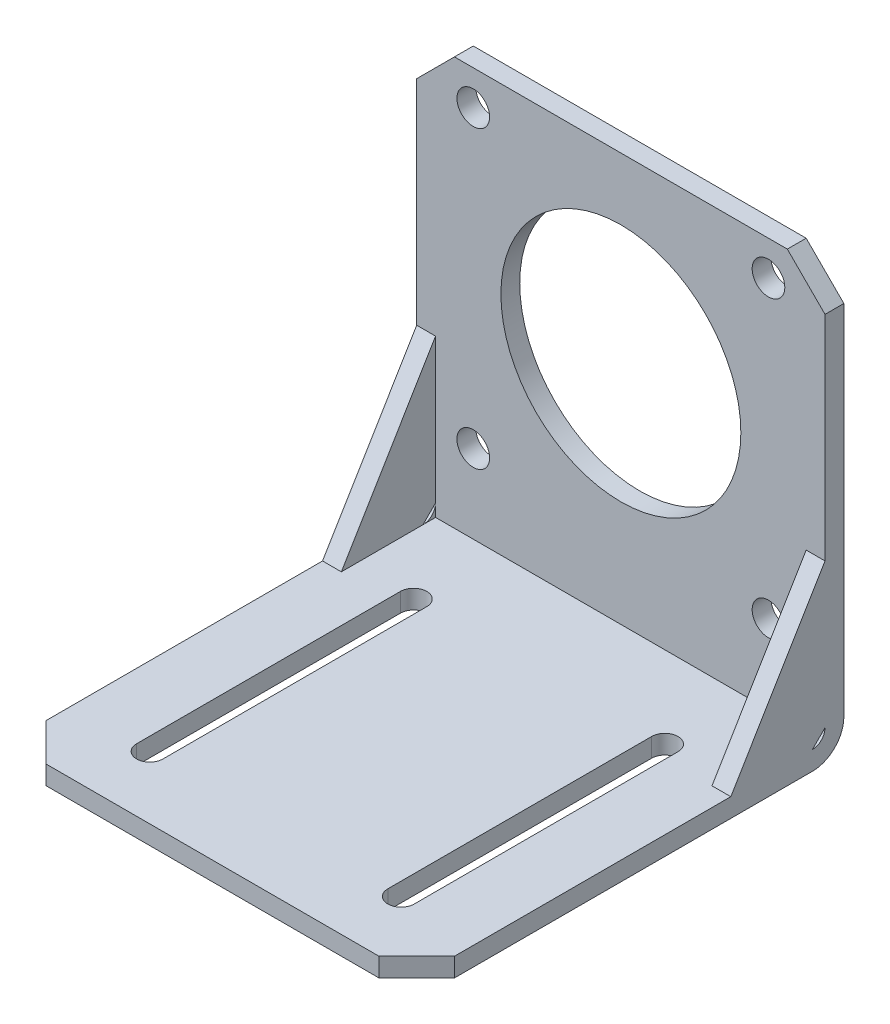
SolidWorks part; units mm, degrees
ref_plane "Front Plane" through (0, 0, 0) normal (0, 0, 1) x (1, 0, 0)
ref_plane "Top Plane" through (0, 0, 0) normal (0, 1, 0) x (1, 0, 0)
ref_plane "Right Plane" through (0, 0, 0) normal (1, 0, 0) x (0, 0, -1)
sketch "Sketch1" plane through (0, 0, 0) normal (0, 0, 1) x (1, 0, 0)
  line L0 (0, 65) -> (0, 36) construction
  line L1 (-32.5, 59) -> (-32.5, 0)
  line L2 (32.5, -65) -> (32.5, 65) construction
  line L3 (32.5, 65) -> (-32.5, 65) construction
  line L4 (-32.5, -65) -> (-32.5, 65) construction
  line L5 (32.5, -65) -> (-32.5, 65) construction
  line L6 (32.5, 65) -> (-32.5, -65) construction
  line L7 (-32.5, 65) -> (-23.5, 65) construction
  line L8 (32.5, 65) -> (23.5, 65) construction
  line L9 (-32.5, 0) -> (32.5, 0)
  line L10 (23.5, 59.5) -> (-23.5, 59.5) construction
  line L11 (23.5, 59.5) -> (23.5, 12.5) construction
  line L12 (23.5, 12.5) -> (-23.5, 12.5) construction
  line L13 (-23.5, 59.5) -> (-23.5, 12.5) construction
  line L14 (23.5, 59.5) -> (-23.5, 12.5) construction
  line L15 (23.5, 12.5) -> (-23.5, 59.5) construction
  line L16 (32.5, 0) -> (32.5, 59)
  line L33 (32.5, 65) -> (26.5, 65) construction
  line L34 (32.5, 65) -> (32.5, 59) construction
  line L35 (32.5, 59) -> (26.5, 65)
  line L36 (-32.5, 65) -> (-26.5, 65) construction
  line L37 (-32.5, 65) -> (-32.5, 59) construction
  line L38 (-32.5, 59) -> (-26.5, 65)
  line L39 (-26.5, 65) -> (26.5, 65)
  line L43 (-32.5, 65) -> (-32.5, 0) construction
  line L44 (-32.5, 0) -> (32.5, 0) construction
  circle A0 centre (0, 36) radius 19.1
  circle A1 centre (-23.5, 59.5) radius 2.6
  circle A2 centre (23.5, 59.5) radius 2.6
  circle A3 centre (23.5, 12.5) radius 2.6
  circle A4 centre (-23.5, 12.5) radius 2.6
  point P0 (0, 0)
extrude "Boss-Extrude1" add sketch "Sketch1" along normal blind 3
sketch "Sketch2" plane through (-32.5, 0, 0) normal (-1, 0, 0) x (0, 0, 1)
  line L0 (0, 0) -> (0, -3)
  line L1 (0, -3) -> (68, -3)
  line L2 (68, -3) -> (68, 0)
  line L3 (68, 0) -> (0, 0)
extrude "Boss-Extrude2" add sketch "Sketch2" against normal blind 65
sketch "Sketch3" plane through (-32.5, 0, 0) normal (-1, 0, 0) x (0, 0, 1)
  line L0 (3, 0) -> (18, 0) construction
  line L1 (68, 0) -> (3, 0) construction
  line L2 (3, 0) -> (3, 25) construction
  line L3 (3, 59) -> (3, 0) construction
  line L4 (3, 25) -> (18, 0)
  line L5 (18, 0) -> (3, 0)
  line L6 (3, 0) -> (3, 25)
extrude "Boss-Extrude3" add sketch "Sketch3" against normal blind 3
sketch "Sketch4" plane through (32.5, 0, 0) normal (1, 0, 0) x (0, 0, -1)
  line L0 (-3, 0) -> (-18, 0)
  line L1 (-68, 0) -> (-3, 0) construction
  line L2 (-3, 0) -> (-3, 25)
  line L3 (-3, 0) -> (-3, 59) construction
  line L4 (-3, 25) -> (-18, 0)
extrude "Boss-Extrude4" add sketch "Sketch4" against normal blind 3
sketch "Sketch5" plane through (0, 0, 0) normal (0, 1, 0) x (1, 0, 0)
  line L0 (-32.5, -68) -> (-32.5, -62)
  line L1 (-32.5, -68) -> (-32.5, -18) construction
  line L2 (-32.5, -62) -> (-26.5, -68)
  line L3 (32.5, -68) -> (-32.5, -68) construction
  line L4 (-26.5, -68) -> (-32.5, -68)
  line L5 (32.5, -68) -> (32.5, -62)
  line L6 (32.5, -68) -> (32.5, -18) construction
  line L7 (32.5, -62) -> (26.5, -68)
  line L8 (26.5, -68) -> (32.5, -68)
  line L9 (-32.5, -68) -> (-20, -68) construction
  line L10 (-20, -68) -> (-20, -58) construction
  line L11 (-20, -58) -> (20, -58) construction
  line L12 (-20, -58) -> (-20, -16) construction
  line L13 (17.9, -58) -> (17.9, -16)
  line L14 (-22.1, -58) -> (-22.1, -16)
  line L15 (-17.9, -58) -> (-17.9, -16)
  line L16 (20, -58) -> (20, -16) construction
  line L17 (22.1, -58) -> (22.1, -16)
  arc A0 (-22.1, -58) -> (-17.9, -58) centre (-20, -58) ccw
  arc A1 (-17.9, -16) -> (-22.1, -16) centre (-20, -16) ccw
  arc A2 (17.9, -58) -> (22.1, -58) centre (20, -58) ccw
  arc A3 (22.1, -16) -> (17.9, -16) centre (20, -16) ccw
  point P17 (20, -37)
  point P20 (-20, -37)
extrude "Cut-Extrude1" cut sketch "Sketch5" against normal blind 3
sketch "Sketch6" plane through (-32.5, 0, 0) normal (-1, 0, 0) x (0, 0, 1)
  line L0 (0, -3) -> (5, -3)
  line L1 (0, -3) -> (62, -3) construction
  line L2 (0, -3) -> (0, 2)
  line L3 (0, 59) -> (0, -3) construction
  line L4 (18, 0) -> (5.0026, 0) construction
  line L5 (18, 0) -> (3, 25) construction
  line L6 (62, 0) -> (18, 0) construction
  line L9 (3.0026, 2) -> (5.0026, 0)
  arc A0 (5, -3) -> (0, 2) centre (5, 2) cw
  arc A1 (5.0026, 0) -> (3.0026, 2) centre (5.0026, 2) cw
extrude "Cut-Extrude2" cut sketch "Sketch6" against normal blind 65
